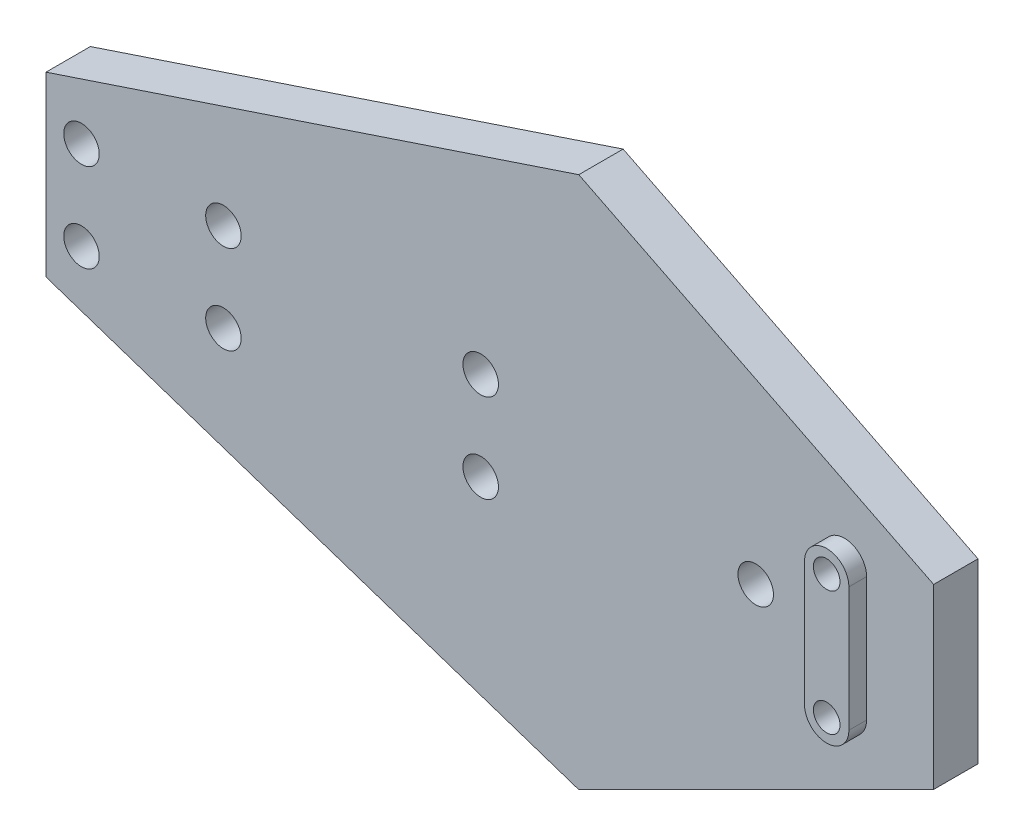
SolidWorks part; units mm, degrees
ref_plane "前视基准面" through (0, 0, 0) normal (0, 0, 1) x (1, 0, 0)
ref_plane "上视基准面" through (0, 0, 0) normal (0, 1, 0) x (1, 0, 0)
ref_plane "右视基准面" through (0, 0, 0) normal (1, 0, 0) x (0, 0, -1)
sketch "草图1" plane through (0, 0, 0) normal (0, 0, 1) x (1, 0, 0)
  line L0 (0, 0) -> (60.0337, -20.0112)
  line L1 (2.75, 0) -> (-2.75, 0) construction
  line L2 (60.0337, -20.0112) -> (100.0562, 0)
  line L3 (100.0562, 0) -> (100.0562, 20.0158)
  line L4 (100.0562, 20.0158) -> (60.0562, 40.0158)
  line L5 (60.0562, 40.0158) -> (0, 19.997)
  line L6 (0, -55) -> (0, 55) construction
  line L7 (0, 19.997) -> (0, 0)
  circle A0 centre (20, 5) radius 2
  circle A1 centre (20, 15) radius 2
  circle A2 centre (49, 5) radius 2
  circle A3 centre (49, 15) radius 2
  circle A4 centre (90, 17) radius 1.5
  circle A5 centre (90, 3) radius 1.5
sketch "草图2" plane through (0, 0, 0) normal (0, 0, 1) x (1, 0, 0)
  circle A0 centre (80, 10) radius 2
  circle A1 centre (4, 5) radius 2
  circle A2 centre (4, 15) radius 2
extrude "凸台-拉伸1" add sketch "草图1" along normal mid plane 5
extrude "切除-拉伸1" cut sketch "草图2" against normal mid plane 5
sketch "草图3" plane through (0, 0, 2.5) normal (0, 0, 1) x (1, 0, 0)
  line L0 (80, 10) -> (96.8291, 10) construction
  line L1 (90, 17) -> (90, 3) construction
  line L2 (92.5, 17) -> (92.5, 3)
  line L3 (87.5, 17) -> (87.5, 3)
  circle A0 centre (90, 17) radius 1.5
  circle A1 centre (90, 3) radius 1.5
  arc A2 (92.5, 17) -> (87.5, 17) centre (90, 17) ccw
  arc A3 (87.5, 3) -> (92.5, 3) centre (90, 3) ccw
  point P5 (90, 10)
  point P12 (0, 0)
  point P13 (0, 0)
  point P14 (0, 0)
extrude "凸台-拉伸2" add sketch "草图3" along normal blind 2
